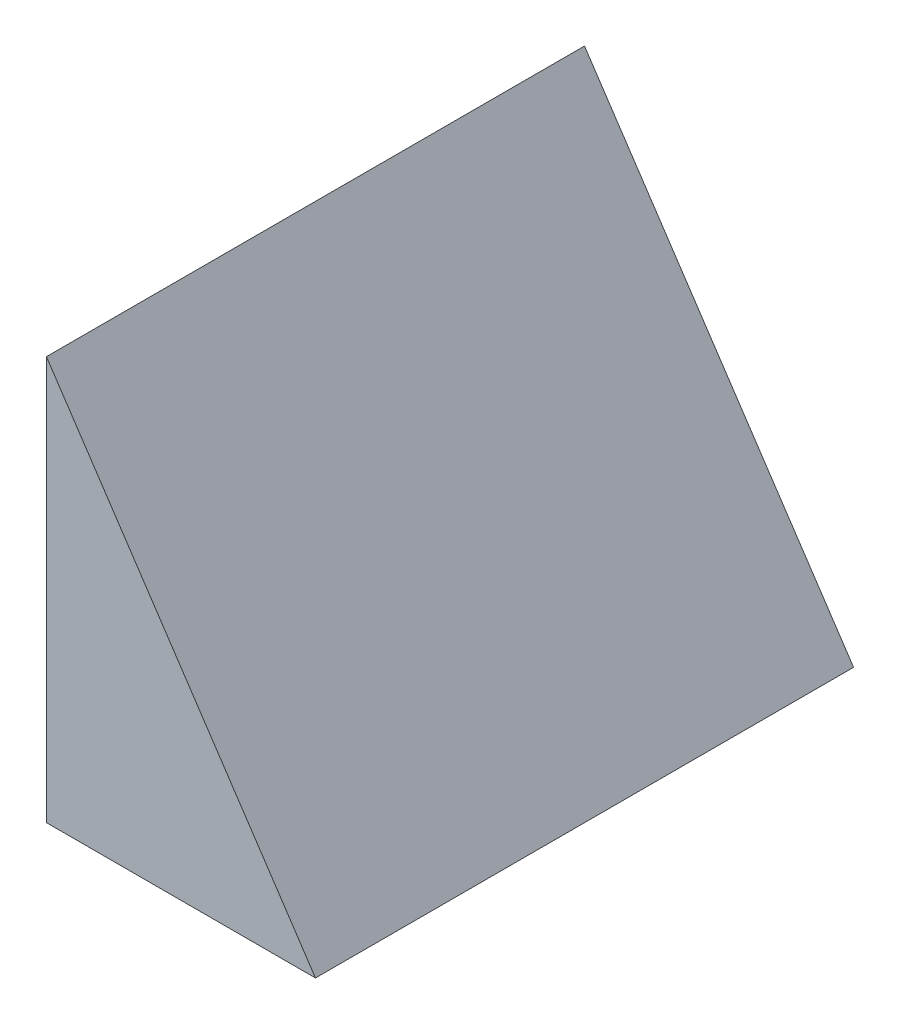
SolidWorks part; units mm, degrees
ref_plane "Alzado" through (0, 0, 0) normal (0, 0, 1) x (1, 0, 0)
ref_plane "Planta" through (0, 0, 0) normal (0, 1, 0) x (1, 0, 0)
ref_plane "Vista lateral" through (0, 0, 0) normal (1, 0, 0) x (0, 0, -1)
sketch "Croquis1" plane through (0, 0, 0) normal (0, 0, 1) x (1, 0, 0)
  line L0 (0, 0) -> (10, 0)
  line L1 (10, 0) -> (0, 15)
  line L2 (0, 15) -> (0, 0)
  dimension "D1" = 10
  dimension "D2" = 15
extrude "Wedge 10 15 20" add sketch "Croquis1" along normal blind 20
